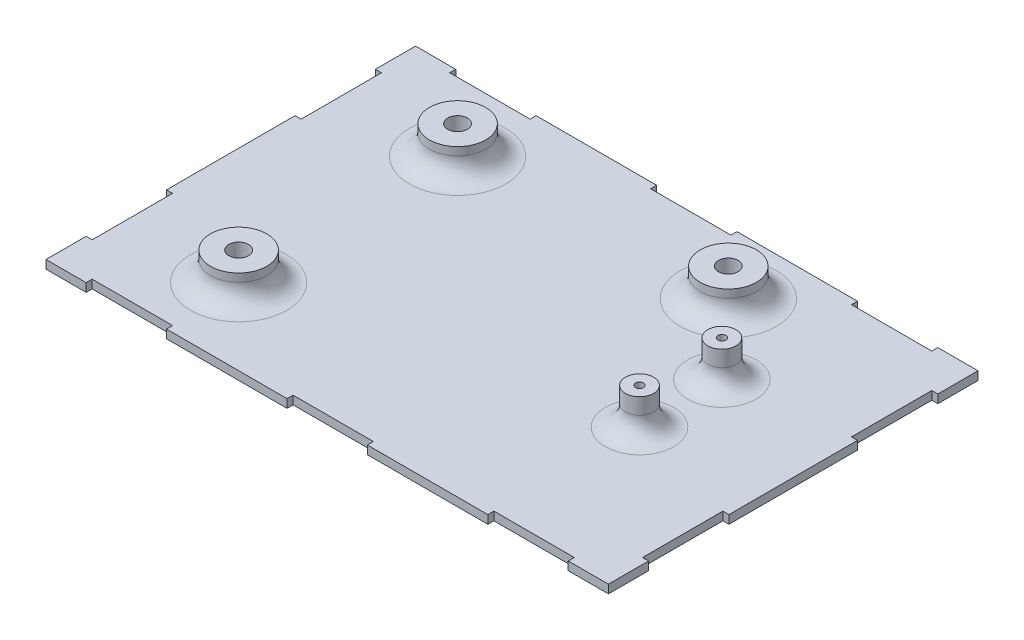
SolidWorks part; units mm, degrees
ref_plane "Front Plane" through (0, 0, 0) normal (0, 0, 1) x (1, 0, 0)
ref_plane "Top Plane" through (0, 0, 0) normal (0, 1, 0) x (1, 0, 0)
ref_plane "Right Plane" through (0, 0, 0) normal (1, 0, 0) x (0, 0, -1)
sketch "Sketch1" plane through (0, 0, 0) normal (0, 1, 0) x (1, 0, 0)
  line L1 (-70, -46) -> (70, -46)
  line L2 (-70, -46) -> (-70, 46)
  line L3 (-70, 46) -> (70, 46)
  line L4 (70, -46) -> (70, 46)
  line L5 (-70, -46) -> (70, 46) construction
  line L6 (-70, 46) -> (70, -46) construction
  point P0 (0, 0)
  dimension "D1" = 140
  dimension "D2" = 92
extrude "Boss-Extrude1" add sketch "Sketch1" along normal blind 2.1
sketch "Sketch2" plane through (0, 2.1, 0) normal (0, 1, 0) x (1, 0, 0)
  line L5 (70, -46) -> (70, 46) construction
  line L12 (70, 36) -> (68.5, 36)
  line L13 (68.5, 36) -> (68.5, 16)
  line L14 (70, 16) -> (70, 36)
  line L15 (68.5, 16) -> (70, 16)
  line L16 (70, -16) -> (68.5, -16)
  line L17 (68.5, -16) -> (68.5, -36)
  line L18 (68.5, -36) -> (70, -36)
  line L19 (70, -36) -> (70, -16)
  line L20 (70, 46) -> (-70, 46) construction
  line L21 (-70, -46) -> (70, -46) construction
  line L22 (60, -46) -> (60, -44.5)
  line L23 (60, -44.5) -> (40, -44.5)
  line L24 (40, -44.5) -> (40, -46)
  line L25 (-60, -46) -> (-60, -44.5)
  line L26 (-60, -44.5) -> (-40, -44.5)
  line L27 (-40, -44.5) -> (-40, -46)
  line L28 (-40, -46) -> (-60, -46)
  line L29 (40, -46) -> (60, -46)
  line L30 (-70, 46) -> (-70, -46) construction
  line L31 (-10, -46) -> (-10, -44.5)
  line L32 (-10, -44.5) -> (10, -44.5)
  line L33 (10, -44.5) -> (10, -46)
  line L34 (10, -46) -> (-10, -46)
  line L35 (-60, 46) -> (-60, 44.5)
  line L36 (-60, 44.5) -> (-40, 44.5)
  line L37 (-40, 44.5) -> (-40, 46)
  line L38 (-40, 46) -> (-60, 46)
  line L39 (-10, 46) -> (-10, 44.5)
  line L40 (-10, 44.5) -> (10, 44.5)
  line L41 (10, 44.5) -> (10, 46)
  line L42 (10, 46) -> (-10, 46)
  line L43 (40, 46) -> (40, 44.5)
  line L44 (40, 44.5) -> (60, 44.5)
  line L45 (60, 44.5) -> (60, 46)
  line L46 (60, 46) -> (40, 46)
  line L47 (-70, 36) -> (-68.5, 36)
  line L48 (-68.5, 36) -> (-68.5, 16)
  line L49 (-68.5, 16) -> (-70, 16)
  line L50 (-70, 16) -> (-70, 36)
  line L51 (-70, -36) -> (-68.5, -36)
  line L52 (-68.5, -36) -> (-68.5, -16)
  line L53 (-68.5, -16) -> (-70, -16)
  line L54 (-70, -16) -> (-70, -36)
  dimension "D1" = 10
  dimension "D2" = 10
  dimension "D3" = 20
  dimension "D4" = 20
  dimension "D5" = 1.5
  dimension "D6" = 1.5
  dimension "D7" = 10
  dimension "D8" = 10
  dimension "D9" = 20
  dimension "D10" = 20
  dimension "D11" = 1.5
  dimension "D12" = 1.5
  dimension "D13" = 1.5
  dimension "D14" = 20
  dimension "D15" = 30
  dimension "D16" = 1.5
  dimension "D17" = 1.5
  dimension "D18" = 1.5
  dimension "D19" = 1.5
  dimension "D20" = 1.5
  dimension "D21" = 20
  dimension "D22" = 20
  dimension "D23" = 20
  dimension "D24" = 20
  dimension "D25" = 20
extrude "Cut-Extrude1" cut sketch "Sketch2" against normal through all
sketch "Sketch3" plane through (0, 2.1, 0) normal (0, 1, 0) x (1, 0, 0)
  line L0 (-70, 46) -> (-70, 36) construction
  line L1 (-60, 44.5) -> (-40, 44.5) construction
  line L3 (70, -16) -> (70, 16) construction
  line L4 (40, 46) -> (10, 46) construction
  circle A0 centre (-41.05, 27.5) radius 7
  circle A1 centre (-41.05, -27) radius 7
  circle A2 centre (23.35, 30.5) radius 7
  circle A3 centre (40, 12.25) radius 3.5
  circle A4 centre (40, -8.25) radius 3.5
  dimension "D3" = 14
  dimension "D4" = 14
  dimension "D6" = 14
  dimension "D14" = 7
  dimension "D15" = 7
  dimension "D1" = 28.95
  dimension "D2" = 17
  dimension "D5" = 54.5
  dimension "D7" = 64.4
  dimension "D8" = 0
  dimension "D9" = 3
  dimension "D10" = 30
  dimension "D11" = 30
  dimension "D12" = 33.75
  dimension "D13" = 20.5
extrude "Boss-Extrude2" add sketch "Sketch3" along normal blind 7
sketch "Sketch6" plane through (0, 9.1, 0) normal (0, 1, 0) x (1, 0, 0)
  circle A0 centre (40, 12.25) radius 3.5
  circle A1 centre (40, -8.25) radius 3.5
  dimension "D1" = 7
  dimension "D2" = 7
extrude "Boss-Extrude3" add sketch "Sketch6" along normal blind 2
sketch "Sketch7" plane through (0, 9.1, 0) normal (0, 1, 0) x (1, 0, 0)
  circle A0 centre (-41.05, 27.5) radius 2.45
  circle A2 centre (23.35, 30.5) radius 2.45
  circle A3 centre (-41.05, -27) radius 2.45
  dimension "D1" = 4.9
  dimension "D2" = 4.9
  dimension "D3" = 4.9
extrude "Cut-Extrude4" cut sketch "Sketch7" against normal blind 5.1
sketch "Sketch8" plane through (0, 11.1, 0) normal (0, 1, 0) x (1, 0, 0)
  circle A0 centre (40, 12.25) radius 1
  circle A1 centre (40, -8.25) radius 1
  dimension "D1" = 2
  dimension "D2" = 2
extrude "Cut-Extrude5" cut sketch "Sketch8" against normal blind 7
fillet "Fillet1" radius 5 5 edges at (40, 2.1, 4.75) (40, 2.1, -15.75) (23.35, 2.1, -37.5) (-41.05, 2.1, 20) (-41.05, 2.1, -34.5)
